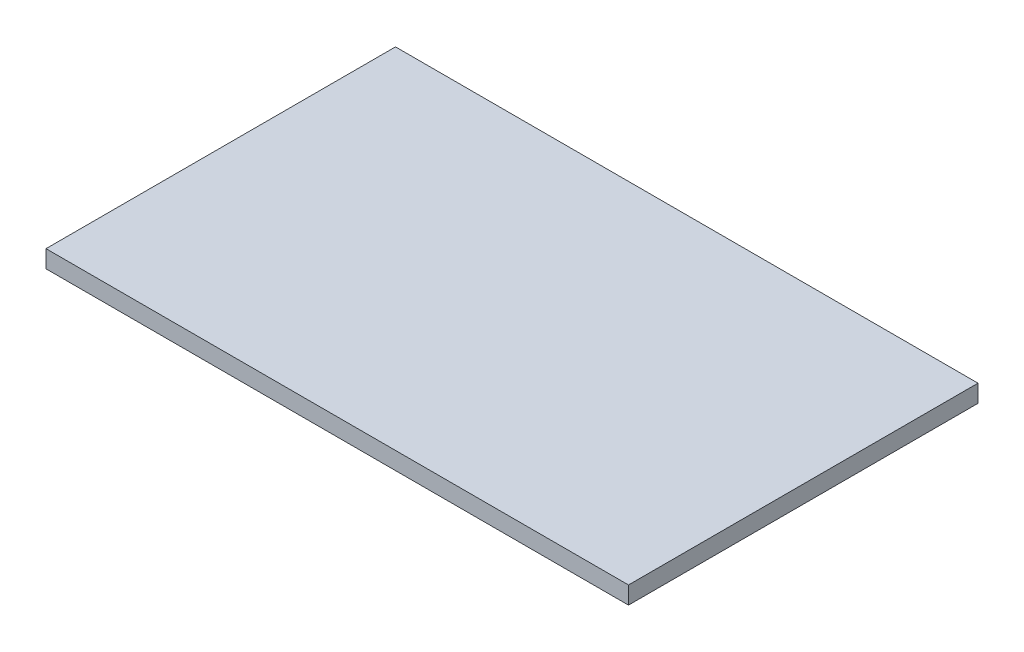
SolidWorks part; units mm, degrees
ref_plane "Front Plane" through (0, 0, 0) normal (0, 0, 1) x (1, 0, 0)
ref_plane "Top Plane" through (0, 0, 0) normal (0, 1, 0) x (1, 0, 0)
ref_plane "Right Plane" through (0, 0, 0) normal (1, 0, 0) x (0, 0, -1)
sketch "Sketch1" plane through (0, 0, 0) normal (0, 1, 0) x (1, 0, 0)
  line L1 (0, 0) -> (100, 0)
  line L2 (0, 0) -> (0, 60)
  line L3 (0, 60) -> (100, 60)
  line L4 (100, 0) -> (100, 60)
  dimension "D1" = 60
  dimension "D2" = 100
extrude "Boss-Extrude1" add sketch "Sketch1" along normal blind 3
